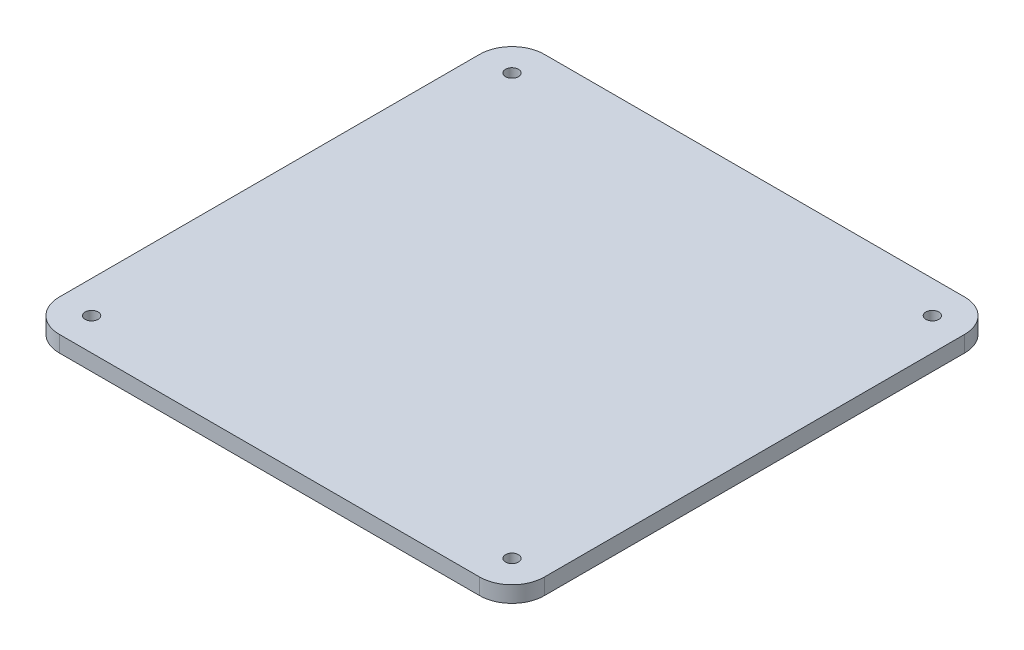
SolidWorks part; units mm, degrees
ref_plane "Front Plane" through (0, 0, 0) normal (0, 0, 1) x (1, 0, 0)
ref_plane "Top Plane" through (0, 0, 0) normal (0, 1, 0) x (1, 0, 0)
ref_plane "Right Plane" through (0, 0, 0) normal (1, 0, 0) x (0, 0, -1)
sketch "Sketch1" plane through (0, 0, 0) normal (0, 1, 0) x (1, 0, 0)
  line L1 (-75, -75) -> (75, -75)
  line L2 (-75, -75) -> (-75, 75)
  line L3 (-75, 75) -> (75, 75)
  line L4 (75, -75) -> (75, 75)
  line L5 (-75, -75) -> (75, 75) construction
  line L6 (-75, 75) -> (75, -75) construction
  point P0 (0, 0)
extrude "Boss-Extrude1" add sketch "Sketch1" along normal blind 5 contours L2 L1 L4 L3
fillet "Fillet1" radius 10 4 edges at (-75, 2.5, -75) (75, 2.5, -75) (75, 2.5, 75) (-75, 2.5, 75)
sketch "Sketch2" plane through (0, 5, 0) normal (0, 1, 0) x (1, 0, 0)
  line L0 (-75, -65) -> (-75, 65) construction
  line L1 (-65, 75) -> (65, 75) construction
  line L2 (75, -65) -> (75, 65) construction
  line L3 (-65, -75) -> (65, -75) construction
  circle A0 centre (65, 65) radius 2
  circle A1 centre (-65, 65) radius 2
  circle A2 centre (-65, -65) radius 2
  circle A3 centre (65, -65) radius 2
  dimension "D1" = 10
  dimension "D2" = 10
  dimension "D3" = 10
  dimension "D4" = 10
  dimension "D5" = 10
  dimension "D6" = 10
  dimension "D7" = 10
  dimension "D8" = 10
extrude "Cut-Extrude1" cut sketch "Sketch2" against normal through all
